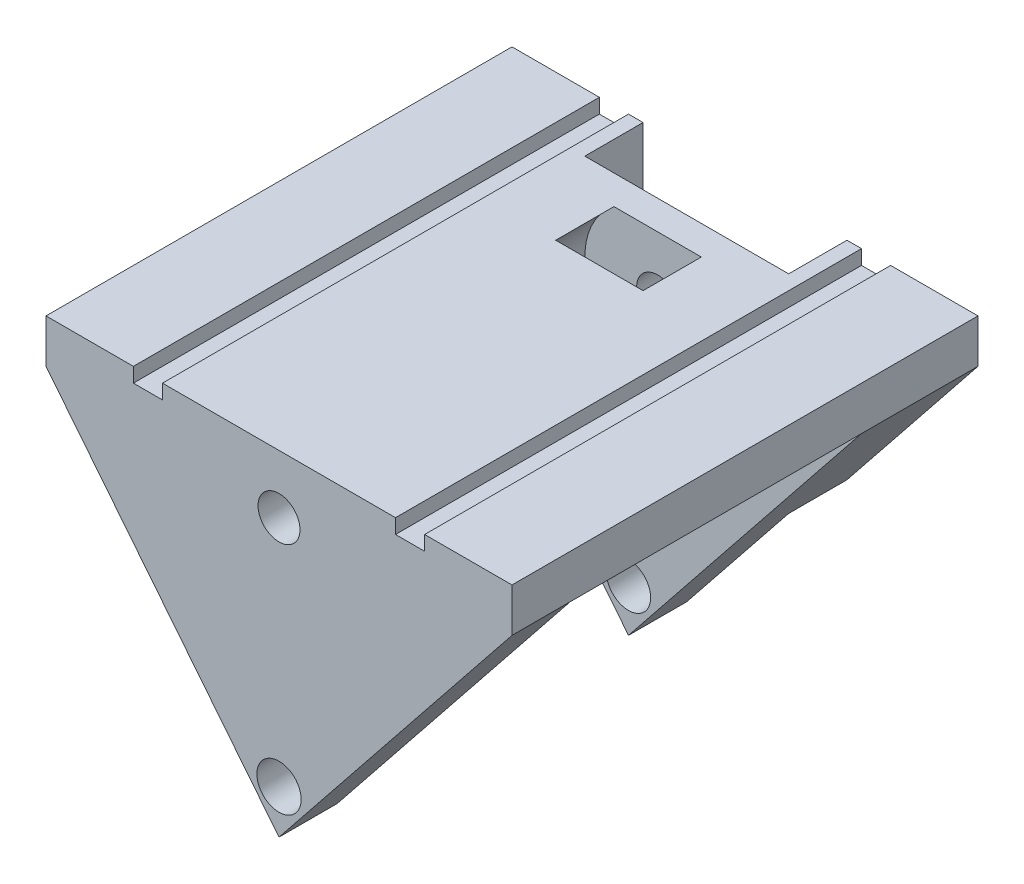
SolidWorks part; units mm, degrees
ref_plane "Front Plane" through (0, 0, 0) normal (0, 0, 1) x (1, 0, 0)
ref_plane "Top Plane" through (0, 0, 0) normal (0, 1, 0) x (1, 0, 0)
ref_plane "Right Plane" through (0, 0, 0) normal (1, 0, 0) x (0, 0, -1)
sketch "Sketch2" plane through (0, 0, 0) normal (0, 1, 0) x (1, 0, 0)
  line L1 (0, 0) -> (50.8, 0)
  line L2 (0, 0) -> (0, 50.8)
  line L3 (0, 50.8) -> (50.8, 50.8)
  line L4 (50.8, 0) -> (50.8, 50.8)
  dimension "D1" = 50.8
  dimension "D2" = 50.8
extrude "Boss-Extrude1" add sketch "Sketch2" along normal blind 4.7625
sketch "Sketch3" plane through (0, 4.7625, 0) normal (0, 1, 0) x (1, 0, 0)
  line L0 (50.8, 50.8) -> (0, 50.8) construction
  line L1 (9.525, 50.8) -> (12.7, 50.8)
  line L2 (9.525, 50.8) -> (9.525, 0)
  line L3 (9.525, 0) -> (12.7, 0)
  line L4 (12.7, 50.8) -> (12.7, 0)
  line L5 (0, 0) -> (50.8, 0) construction
  line L6 (0, 50.8) -> (0, 0) construction
  line L7 (38.1, 50.8) -> (41.275, 50.8)
  line L8 (38.1, 50.8) -> (38.1, 0)
  line L9 (38.1, 0) -> (41.275, 0)
  line L10 (41.275, 50.8) -> (41.275, 0)
  line L11 (50.8, 0) -> (50.8, 50.8) construction
  dimension "D1" = 3.175
  dimension "D2" = 3.175
  dimension "D3" = 9.525
  dimension "D4" = 9.525
extrude "Cut-Extrude1" cut sketch "Sketch3" against normal blind 1.5875
sketch "Sketch4" plane through (0, 0, 0) normal (0, 0, 1) x (1, 0, 0)
  line L0 (0, 0) -> (25.4, 0)
  line L1 (0, 0) -> (50.8, 0) construction
  line L2 (25.4, 0) -> (25.4, -31.75)
  line L3 (25.4, -31.75) -> (0, 0)
  line L4 (25.4, -31.75) -> (50.8, 0)
  line L5 (25.4, 0) -> (50.8, 0)
  line M8 (0, 0) -> (50.8, 0)
  dimension "D1" = 31.75
extrude "Boss-Extrude2" add sketch "Sketch4" against normal blind 6.35 contours L2 L4 M8 | L3 L2 M8
sketch "Sketch5" plane through (0, 0, -50.8) normal (0, 0, -1) x (-1, 0, 0)
  line L0 (-50.8, 0) -> (-25.4, 0)
  line L1 (-50.8, 4.7625) -> (-50.8, 0) construction
  line L2 (-50.8, 0) -> (0, 0) construction
  line L3 (-25.4, 0) -> (-25.4, -31.75)
  line L4 (-25.4, -31.75) -> (-50.8, 0) construction
  line L5 (-25.4, -31.75) -> (0, 0) construction
  line L6 (-25.4, -31.75) -> (-50.8, 0)
  line L7 (0, 0) -> (-25.4, 0)
  line L8 (-25.4, 0) -> (-25.4, -31.75)
  line L9 (0, 0) -> (-25.4, -31.75)
  line M14 (-50.8, 0) -> (0, 0)
extrude "Boss-Extrude3" add sketch "Sketch5" against normal blind 12.7 contours L6 L3 M14 | L9 L3 M14
sketch "Sketch6" plane through (0, 4.7625, 0) normal (0, 1, 0) x (1, 0, 0)
  line L0 (38.1, 50.8) -> (12.7, 50.8) construction
  line L1 (14.2875, 50.8) -> (36.5125, 50.8)
  line L2 (14.2875, 50.8) -> (14.2875, 44.45)
  line L3 (14.2875, 44.45) -> (36.5125, 44.45)
  line L4 (36.5125, 50.8) -> (36.5125, 44.45)
  line L5 (0, 50.8) -> (0, 0) construction
  dimension "D1" = 22.225
  dimension "D2" = 14.2875
  dimension "D3" = 6.35
extrude "Cut-Extrude2" cut sketch "Sketch6" against normal blind 44.45
sketch "Sketch7" plane through (0, 0, -44.45) normal (0, 0, -1) x (-1, 0, 0)
  line L0 (-14.2875, 4.7625) -> (-36.5125, 4.7625) construction
  line L2 (-50.8, 4.7625) -> (-50.8, 0) construction
  circle A0 centre (-25.4, -26.9875) radius 2.413
  circle A1 centre (-25.4, -1.5875) radius 2.286
  dimension "D1" = 25.4
  dimension "D3" = 25.4
  dimension "D2" = 31.75
  dimension "D4" = 25.4
extrude "Cut-Extrude3" cut sketch "Sketch7" against normal blind 50.8
sketch "Sketch8" plane through (0, 0, -38.1) normal (0, 0, 1) x (1, 0, 0)
  circle A0 centre (25.4, -1.5875) radius 7.9375
  circle A1 centre (25.4, -1.5875) radius 2.286 construction
  dimension "D1" = 0
extrude "Cut-Extrude4" cut sketch "Sketch8" along normal blind 3.175 and the other way blind 3.175
